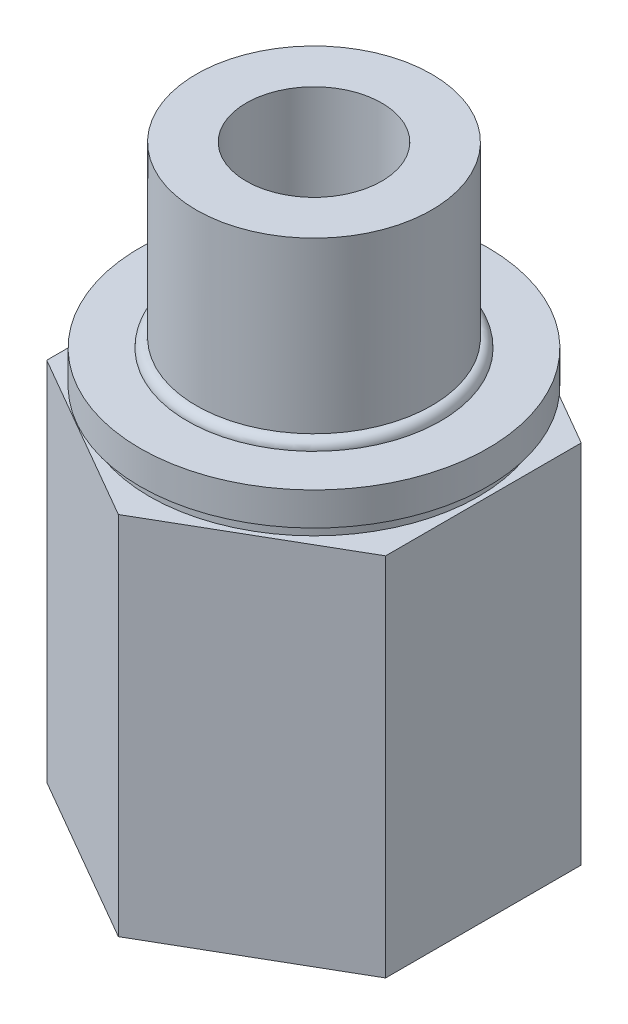
SolidWorks part; units mm, degrees
material "Plain Carbon Steel"
ref_plane "Front Plane" through (0, 0, 0) normal (0, 0, 1) x (1, 0, 0)
ref_plane "Top Plane" through (0, 0, 0) normal (0, 1, 0) x (1, 0, 0)
ref_plane "Right Plane" through (0, 0, 0) normal (1, 0, 0) x (0, 0, -1)
sketch "Sketch1" plane through (0, 0, 0) normal (0, 1, 0) x (1, 0, 0)
  line L1 (-9.5, 5.4848) -> (-9.5, -5.4848)
  line L2 (-9.5, -5.4848) -> (0, -10.9697)
  line L3 (0, -10.9697) -> (9.5, -5.4848)
  line L4 (9.5, -5.4848) -> (9.5, 5.4848)
  line L5 (9.5, 5.4848) -> (0, 10.9697)
  line L6 (0, 10.9697) -> (-9.5, 5.4848)
  circle A0 centre (0, 0) radius 9.5 construction
  dimension "D1" = 19
extrude "Boss-Extrude1" add sketch "Sketch1" along normal blind 20.5 contours L6 L1 L2 L3 L4 L5
sketch "Sketch2" plane through (0, 20.5, 0) normal (0, 1, 0) x (1, 0, 0)
  circle A0 centre (0, 0) radius 9.225
  dimension "D1" = 18.45
extrude "Boss-Extrude2" add sketch "Sketch2" along normal blind 0.75
sketch "Sketch3" plane through (0, 21.25, 0) normal (0, 1, 0) x (1, 0, 0)
  circle A0 centre (0, 0) radius 9.75
  dimension "D1" = 19.5
extrude "Boss-Extrude3" add sketch "Sketch3" along normal blind 1.85 contours A0
sketch "Sketch4" plane through (0, 23.1, 0) normal (0, 1, 0) x (1, 0, 0)
  circle A0 centre (0, 0) radius 6.6
  dimension "D1" = 13.2
extrude "Boss-Extrude4" add sketch "Sketch4" along normal blind 10 contours A0
sketch "Sketch5" plane through (0, 33.1, 0) normal (0, 1, 0) x (1, 0, 0)
  circle A0 centre (0, 0) radius 3.8
  dimension "D1" = 7.6
extrude "Cut-Extrude1" cut sketch "Sketch5" against normal through all contours A0
sketch "Sketch6" plane through (0, 0, 0) normal (0, -1, 0) x (1, 0, 0)
  circle A0 centre (0, 0) radius 5.5
  dimension "D1" = 11
extrude "Cut-Extrude2" cut sketch "Sketch6" against normal blind 16.5 contours A0
sketch "Sketch7" plane through (0, 0, 0) normal (0, 0, 1) x (1, 0, 0)
  line L0 (-6.6, 33.1) -> (-6.6, 23.1) construction
  line L2 (-6.6, 23.6) -> (-6.6, 23.1)
  line L3 (9.75, 23.1) -> (-9.75, 23.1) construction
  line L4 (-6.6, 23.1) -> (-7.1, 23.1)
  arc A0 (-6.6, 23.6) -> (-7.1, 23.1) centre (-6.6, 23.1) ccw
  dimension "D1" = 1
revolve "Revolve1" add sketch "Sketch7" angle 360 about axis through (0, 0, 0) along (0, 1, 0)
